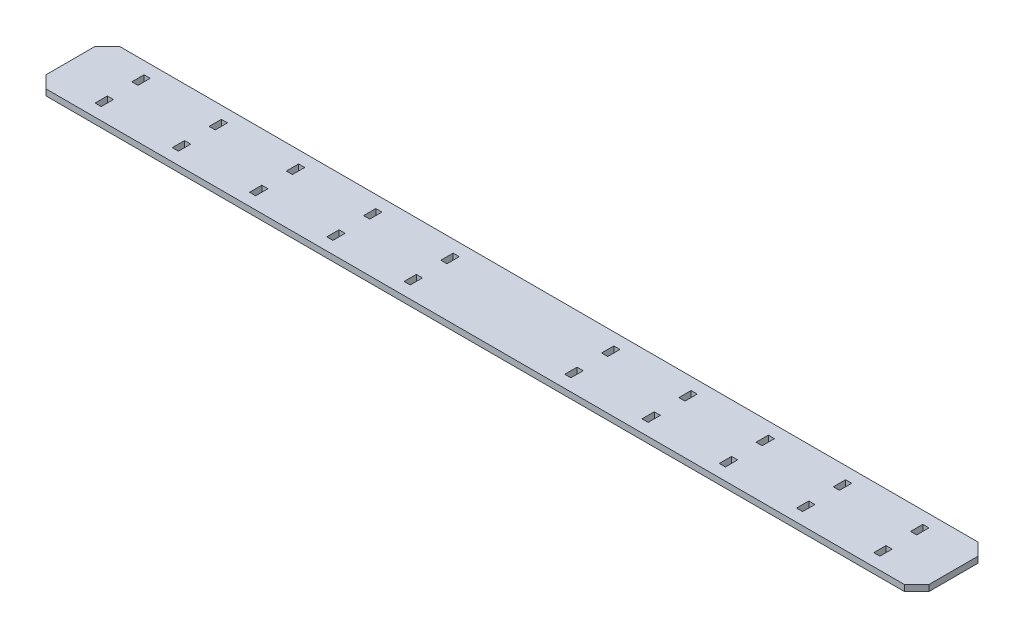
SolidWorks part; units mm, degrees
ref_plane "Front Plane" through (0, 0, 0) normal (0, 0, 1) x (1, 0, 0)
ref_plane "Top Plane" through (0, 0, 0) normal (0, 1, 0) x (1, 0, 0)
ref_plane "Right Plane" through (0, 0, 0) normal (1, 0, 0) x (0, 0, -1)
sketch "Sketch1" plane through (0, 0, 0) normal (0, 1, 0) x (1, 0, 0)
  line L1 (-228.6, -19.05) -> (228.6, -19.05)
  line L2 (-228.6, -19.05) -> (-228.6, 19.05)
  line L3 (-228.6, 19.05) -> (228.6, 19.05)
  line L4 (228.6, -19.05) -> (228.6, 19.05)
  line L5 (-228.6, -19.05) -> (228.6, 19.05) construction
  line L6 (-228.6, 19.05) -> (228.6, -19.05) construction
  point P0 (0, 0)
  dimension "D1" = 457.2
  dimension "D2" = 38.1
extrude "Boss-Extrude1" add sketch "Sketch1" along normal blind 3.175
sketch "Sketch2" plane through (0, 3.175, 0) normal (0, 1, 0) x (1, 0, 0)
  line L0 (-228.6, 0) -> (228.6, 0) construction
  line L1 (-228.6, 19.05) -> (-228.6, -19.05) construction
  line L2 (228.6, -19.05) -> (228.6, 19.05) construction
  line L3 (-203.2, 6.35) -> (-200.025, 6.35)
  line L4 (-203.2, -12.7) -> (-200.025, -12.7)
  line L5 (-203.2, -12.7) -> (-203.2, -6.35)
  line L6 (-203.2, 12.7) -> (-200.025, 12.7)
  line L7 (-200.025, -12.7) -> (-200.025, -6.35)
  line L8 (-203.2, -12.7) -> (-200.025, 12.7) construction
  line L9 (-203.2, 12.7) -> (-200.025, -12.7) construction
  line L10 (-203.2, -6.35) -> (-200.025, -6.35)
  line L11 (0, 19.05) -> (0, -19.05) construction
  line L12 (228.6, 19.05) -> (-228.6, 19.05) construction
  line L13 (-228.6, -19.05) -> (228.6, -19.05) construction
  line L14 (-203.2, 6.35) -> (-203.2, 12.7)
  line L15 (-200.025, 6.35) -> (-200.025, 12.7)
  line L16 (203.2, 12.7) -> (200.025, -12.7) construction
  line L17 (203.2, -12.7) -> (200.025, 12.7) construction
  line L18 (200.025, 6.35) -> (200.025, 12.7)
  line L19 (203.2, 6.35) -> (203.2, 12.7)
  line L20 (203.2, -6.35) -> (200.025, -6.35)
  line L21 (200.025, -12.7) -> (200.025, -6.35)
  line L22 (203.2, 12.7) -> (200.025, 12.7)
  line L23 (203.2, -12.7) -> (203.2, -6.35)
  line L24 (203.2, -12.7) -> (200.025, -12.7)
  line L25 (203.2, 6.35) -> (200.025, 6.35)
  line L26 (-160.025, 6.35) -> (-160.025, 12.7)
  line L27 (-163.2, 12.7) -> (-160.025, 12.7)
  line L28 (-163.2, 6.35) -> (-163.2, 12.7)
  line L29 (-163.2, 6.35) -> (-160.025, 6.35)
  line L30 (-163.2, -12.7) -> (-163.2, -6.35)
  line L31 (-163.2, -6.35) -> (-160.025, -6.35)
  line L32 (-160.025, -12.7) -> (-160.025, -6.35)
  line L33 (-163.2, -12.7) -> (-160.025, -12.7)
  line L34 (-120.025, 6.35) -> (-120.025, 12.7)
  line L35 (-123.2, 12.7) -> (-120.025, 12.7)
  line L36 (-123.2, 6.35) -> (-123.2, 12.7)
  line L37 (-123.2, 6.35) -> (-120.025, 6.35)
  line L38 (-123.2, -12.7) -> (-123.2, -6.35)
  line L39 (-123.2, -6.35) -> (-120.025, -6.35)
  line L40 (-120.025, -12.7) -> (-120.025, -6.35)
  line L41 (-123.2, -12.7) -> (-120.025, -12.7)
  line L42 (-80.025, 6.35) -> (-80.025, 12.7)
  line L43 (-83.2, 12.7) -> (-80.025, 12.7)
  line L44 (-83.2, 6.35) -> (-83.2, 12.7)
  line L45 (-83.2, 6.35) -> (-80.025, 6.35)
  line L46 (-83.2, -12.7) -> (-83.2, -6.35)
  line L47 (-83.2, -6.35) -> (-80.025, -6.35)
  line L48 (-80.025, -12.7) -> (-80.025, -6.35)
  line L49 (-83.2, -12.7) -> (-80.025, -12.7)
  line L50 (-40.025, 6.35) -> (-40.025, 12.7)
  line L51 (-43.2, 12.7) -> (-40.025, 12.7)
  line L52 (-43.2, 6.35) -> (-43.2, 12.7)
  line L53 (-43.2, 6.35) -> (-40.025, 6.35)
  line L54 (-43.2, -12.7) -> (-43.2, -6.35)
  line L55 (-43.2, -6.35) -> (-40.025, -6.35)
  line L56 (-40.025, -12.7) -> (-40.025, -6.35)
  line L57 (-43.2, -12.7) -> (-40.025, -12.7)
  line L58 (43.2, -12.7) -> (40.025, -12.7)
  line L59 (40.025, -12.7) -> (40.025, -6.35)
  line L60 (43.2, -6.35) -> (40.025, -6.35)
  line L61 (43.2, -12.7) -> (43.2, -6.35)
  line L62 (43.2, 6.35) -> (40.025, 6.35)
  line L63 (43.2, 6.35) -> (43.2, 12.7)
  line L64 (43.2, 12.7) -> (40.025, 12.7)
  line L65 (40.025, 6.35) -> (40.025, 12.7)
  line L66 (83.2, -12.7) -> (80.025, -12.7)
  line L67 (80.025, -12.7) -> (80.025, -6.35)
  line L68 (83.2, -6.35) -> (80.025, -6.35)
  line L69 (83.2, -12.7) -> (83.2, -6.35)
  line L70 (83.2, 6.35) -> (80.025, 6.35)
  line L71 (83.2, 6.35) -> (83.2, 12.7)
  line L72 (83.2, 12.7) -> (80.025, 12.7)
  line L73 (80.025, 6.35) -> (80.025, 12.7)
  line L74 (123.2, -12.7) -> (120.025, -12.7)
  line L75 (120.025, -12.7) -> (120.025, -6.35)
  line L76 (123.2, -6.35) -> (120.025, -6.35)
  line L77 (123.2, -12.7) -> (123.2, -6.35)
  line L78 (123.2, 6.35) -> (120.025, 6.35)
  line L79 (123.2, 6.35) -> (123.2, 12.7)
  line L80 (123.2, 12.7) -> (120.025, 12.7)
  line L81 (120.025, 6.35) -> (120.025, 12.7)
  line L82 (163.2, -12.7) -> (160.025, -12.7)
  line L83 (160.025, -12.7) -> (160.025, -6.35)
  line L84 (163.2, -6.35) -> (160.025, -6.35)
  line L85 (163.2, -12.7) -> (163.2, -6.35)
  line L86 (163.2, 6.35) -> (160.025, 6.35)
  line L87 (163.2, 6.35) -> (163.2, 12.7)
  line L88 (163.2, 12.7) -> (160.025, 12.7)
  line L89 (160.025, 6.35) -> (160.025, 12.7)
  point P6 (-201.6125, 0)
  point P29 (201.6125, 0)
  dimension "D1" = 3.175
  dimension "D2" = 25.4
  dimension "D3" = 6.35
  dimension "D4" = 6.35
  dimension "D5" = 25.4
  dimension "D6" = 5
extrude "Cut-Extrude1" cut sketch "Sketch2" against normal blind 6.35
chamfer "Chamfer1" distance 6.35 angle 45 4 edges at (-228.6, 1.5875, -19.05) (-228.6, 1.5875, 19.05) (228.6, 1.5875, -19.05) (228.6, 1.5875, 19.05)
